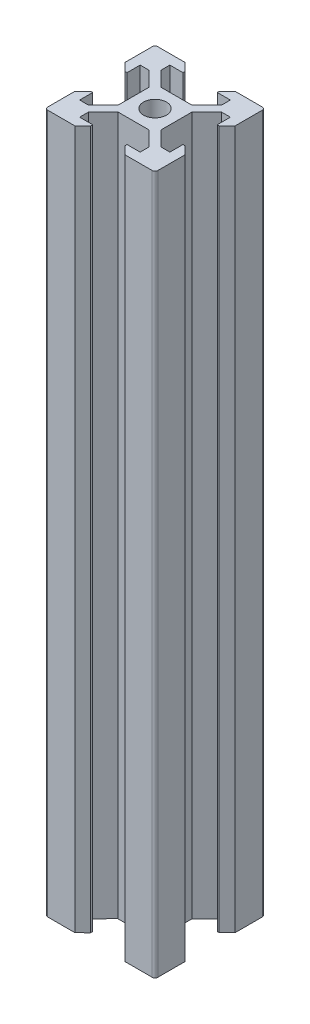
SolidWorks part; units mm, degrees
ref_plane "Front Plane" through (0, 0, 0) normal (0, 0, 1) x (1, 0, 0)
ref_plane "Top Plane" through (0, 0, 0) normal (0, 1, 0) x (1, 0, 0)
ref_plane "Right Plane" through (0, 0, 0) normal (1, 0, 0) x (0, 0, -1)
sketch "Sketch1" plane through (0, 0, 0) normal (1, 0, 0) x (0, 0, -1)
  line L0 (0, 0) -> (0, 127)
  dimension "D1" = 127
other "Vslot2020 2020(5)"
ref_plane "Plane5" through (0, 0, 0) normal (0, 1, 0) x (0, 0, 1)
sketch "Sketch2" plane through (0, 0, 0) normal (0, 1, 0) x (0, 0, 1)
  line L58 (13.9, 7.1491) -> (13.9, 12.8445)
  line L59 (13.9, 12.8445) -> (16.5585, 15.4922)
  line L60 (16.5585, 15.4922) -> (16.5507, 15.5)
  line L61 (16.5507, 15.5) -> (18.2, 15.5)
  line L62 (18.2, 15.5) -> (18.2, 13.12)
  line L63 (18.2, 13.12) -> (18.5344, 13.12)
  line L64 (18.5344, 13.12) -> (20, 14.58)
  line L65 (20, 14.58) -> (20, 19.5)
  line L66 (19.5, 20) -> (14.575, 20)
  line L67 (14.575, 20) -> (13.12, 18.545)
  line L68 (13.12, 18.545) -> (13.12, 18.2)
  line L69 (13.12, 18.2) -> (15.5, 18.2)
  line L70 (15.5, 18.2) -> (15.5, 16.555)
  line L71 (15.5, 16.555) -> (12.8341, 13.9)
  line L72 (12.8341, 13.9) -> (7.155, 13.9)
  line L73 (7.155, 13.9) -> (4.5, 16.555)
  line L74 (4.5, 16.555) -> (4.5, 18.2)
  line L75 (4.5, 18.2) -> (6.875, 18.2)
  line L76 (6.875, 18.2) -> (6.875, 18.545)
  line L77 (6.875, 18.545) -> (5.42, 20)
  line L78 (5.42, 20) -> (0.5, 20)
  line L79 (0, 19.5) -> (0, 14.58)
  line L80 (0, 14.58) -> (1.46, 13.12)
  line L81 (1.46, 13.12) -> (1.8, 13.12)
  line L82 (1.8, 13.12) -> (1.8, 15.5)
  line L83 (1.8, 15.5) -> (3.445, 15.5)
  line L84 (3.445, 15.5) -> (3.4393, 15.4943)
  line L85 (3.4393, 15.4943) -> (6.0943, 12.8393)
  line L86 (6.0943, 12.8393) -> (6.1, 12.845)
  line L87 (6.1, 12.845) -> (6.1, 7.1491)
  line L88 (6.1, 7.1491) -> (3.4393, 4.5)
  line L89 (3.4393, 4.5) -> (1.8, 4.5)
  line L90 (1.8, 4.5) -> (1.8, 6.88)
  line L91 (1.8, 6.88) -> (1.46, 6.88)
  line L92 (1.46, 6.88) -> (0, 5.42)
  line L93 (0, 5.42) -> (0, 0.5)
  line L94 (0.5, 0) -> (5.42, 0)
  line L95 (5.42, 0) -> (6.875, 1.455)
  line L96 (6.875, 1.455) -> (6.875, 1.8)
  line L97 (6.875, 1.8) -> (4.5, 1.8)
  line L98 (4.5, 1.8) -> (4.5, 3.4393)
  line L99 (4.5, 3.4393) -> (7.1583, 6.0861)
  line L100 (7.1583, 6.0861) -> (7.1445, 6.1)
  line L101 (7.1445, 6.1) -> (12.8546, 6.1)
  line L102 (12.8546, 6.1) -> (12.8412, 6.0865)
  line L103 (12.8412, 6.0865) -> (15.4997, 3.4375)
  line L104 (15.4997, 3.4375) -> (15.5, 3.4377)
  line L105 (15.5, 3.4377) -> (15.5, 1.8)
  line L106 (15.5, 1.8) -> (13.12, 1.8)
  line L107 (13.12, 1.8) -> (13.12, 1.455)
  line L108 (13.12, 1.455) -> (14.575, 0)
  line L109 (14.575, 0) -> (19.5, 0)
  line L110 (20, 0.5) -> (20, 5.42)
  line L111 (20, 5.42) -> (18.6069, 6.88)
  line L112 (18.6069, 6.88) -> (18.2, 6.88)
  line L113 (18.2, 6.88) -> (18.2, 4.5)
  line L114 (18.2, 4.5) -> (16.5585, 4.5)
  line L115 (16.5585, 4.5) -> (13.9, 7.1491)
  line L116 (13.9, 7.1491) -> (13.9, 12.8445)
  line L117 (13.9, 12.8445) -> (16.5585, 15.4922)
  line L118 (16.5585, 15.4922) -> (16.5507, 15.5)
  line L119 (16.5507, 15.5) -> (18.2, 15.5)
  line L120 (18.2, 15.5) -> (18.2, 13.12)
  line L121 (18.2, 13.12) -> (18.5344, 13.12)
  line L122 (18.5344, 13.12) -> (20, 14.58)
  line L123 (20, 14.58) -> (20, 19.5)
  line L124 (19.5, 20) -> (14.575, 20)
  line L125 (14.575, 20) -> (13.12, 18.545)
  line L126 (13.12, 18.545) -> (13.12, 18.2)
  line L127 (13.12, 18.2) -> (15.5, 18.2)
  line L128 (15.5, 18.2) -> (15.5, 16.555)
  line L129 (15.5, 16.555) -> (12.8341, 13.9)
  line L130 (12.8341, 13.9) -> (7.155, 13.9)
  line L131 (7.155, 13.9) -> (4.5, 16.555)
  line L132 (4.5, 16.555) -> (4.5, 18.2)
  line L133 (4.5, 18.2) -> (6.875, 18.2)
  line L134 (6.875, 18.2) -> (6.875, 18.545)
  line L135 (6.875, 18.545) -> (5.42, 20)
  line L136 (5.42, 20) -> (0.5, 20)
  line L137 (0, 19.5) -> (0, 14.58)
  line L138 (0, 14.58) -> (1.46, 13.12)
  line L139 (1.46, 13.12) -> (1.8, 13.12)
  line L140 (1.8, 13.12) -> (1.8, 15.5)
  line L141 (1.8, 15.5) -> (3.445, 15.5)
  line L142 (3.445, 15.5) -> (3.4393, 15.4943)
  line L143 (3.4393, 15.4943) -> (6.0943, 12.8393)
  line L144 (6.0943, 12.8393) -> (6.1, 12.845)
  line L145 (6.1, 12.845) -> (6.1, 7.1491)
  line L146 (6.1, 7.1491) -> (3.4393, 4.5)
  line L147 (3.4393, 4.5) -> (1.8, 4.5)
  line L148 (1.8, 4.5) -> (1.8, 6.88)
  line L149 (1.8, 6.88) -> (1.46, 6.88)
  line L150 (1.46, 6.88) -> (0, 5.42)
  line L151 (0, 5.42) -> (0, 0.5)
  line L152 (0.5, 0) -> (5.42, 0)
  line L153 (5.42, 0) -> (6.875, 1.455)
  line L154 (6.875, 1.455) -> (6.875, 1.8)
  line L155 (6.875, 1.8) -> (4.5, 1.8)
  line L156 (4.5, 1.8) -> (4.5, 3.4393)
  line L157 (4.5, 3.4393) -> (7.1583, 6.0861)
  line L158 (7.1583, 6.0861) -> (7.1445, 6.1)
  line L159 (7.1445, 6.1) -> (12.8546, 6.1)
  line L160 (12.8546, 6.1) -> (12.8412, 6.0865)
  line L161 (12.8412, 6.0865) -> (15.4997, 3.4375)
  line L162 (15.4997, 3.4375) -> (15.5, 3.4377)
  line L163 (15.5, 3.4377) -> (15.5, 1.8)
  line L164 (15.5, 1.8) -> (13.12, 1.8)
  line L165 (13.12, 1.8) -> (13.12, 1.455)
  line L166 (13.12, 1.455) -> (14.575, 0)
  line L167 (14.575, 0) -> (19.5, 0)
  line L168 (20, 0.5) -> (20, 5.42)
  line L169 (20, 5.42) -> (18.6069, 6.88)
  line L170 (18.6069, 6.88) -> (18.2, 6.88)
  line L171 (18.2, 6.88) -> (18.2, 4.5)
  line L172 (18.2, 4.5) -> (16.5585, 4.5)
  line L173 (16.5585, 4.5) -> (13.9, 7.1491)
  circle A0 centre (10, 10) radius 2.0746 construction
  circle A1 centre (10, 10) radius 2.0746
  arc A4 (20, 19.5) -> (19.5, 20) centre (19.5, 19.5) ccw
  arc A5 (0.5, 20) -> (0, 19.5) centre (0.5, 19.5) ccw
  arc A6 (0, 0.5) -> (0.5, 0) centre (0.5, 0.5) ccw
  arc A7 (19.5, 0) -> (20, 0.5) centre (19.5, 0.5) ccw
  arc A8 (20, 19.5) -> (19.5, 20) centre (19.5, 19.5) ccw
  arc A9 (0.5, 20) -> (0, 19.5) centre (0.5, 19.5) ccw
  arc A10 (0, 0.5) -> (0.5, 0) centre (0.5, 0.5) ccw
  arc A11 (19.5, 0) -> (20, 0.5) centre (19.5, 0.5) ccw
  point P16 (0, 0)
  dimension "D1" = 0
